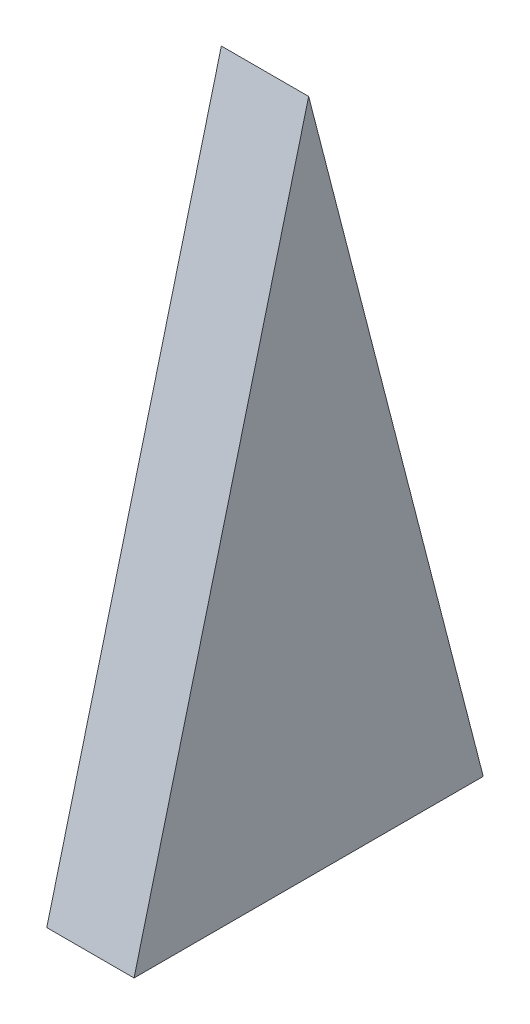
SolidWorks part; units mm, degrees
ref_plane "Plan de face" through (0, 0, 0) normal (0, 0, 1) x (1, 0, 0)
ref_plane "Plan de dessus" through (0, 0, 0) normal (0, 1, 0) x (1, 0, 0)
ref_plane "Plan de droite" through (0, 0, 0) normal (1, 0, 0) x (0, 0, -1)
sketch "Esquisse2" plane through (0, 0, 0) normal (1, 0, 0) x (0, 0, -1)
  line L0 (0, 77.4597) -> (-20, 0)
  line L1 (-20, 0) -> (20, 0)
  line L2 (20, 0) -> (0, 77.4597)
  point P2 (0, 0)
  dimension "D1" = 80
  dimension "D2" = 40
extrude "Boss.-Extru.1" add sketch "Esquisse2" against normal blind 10
